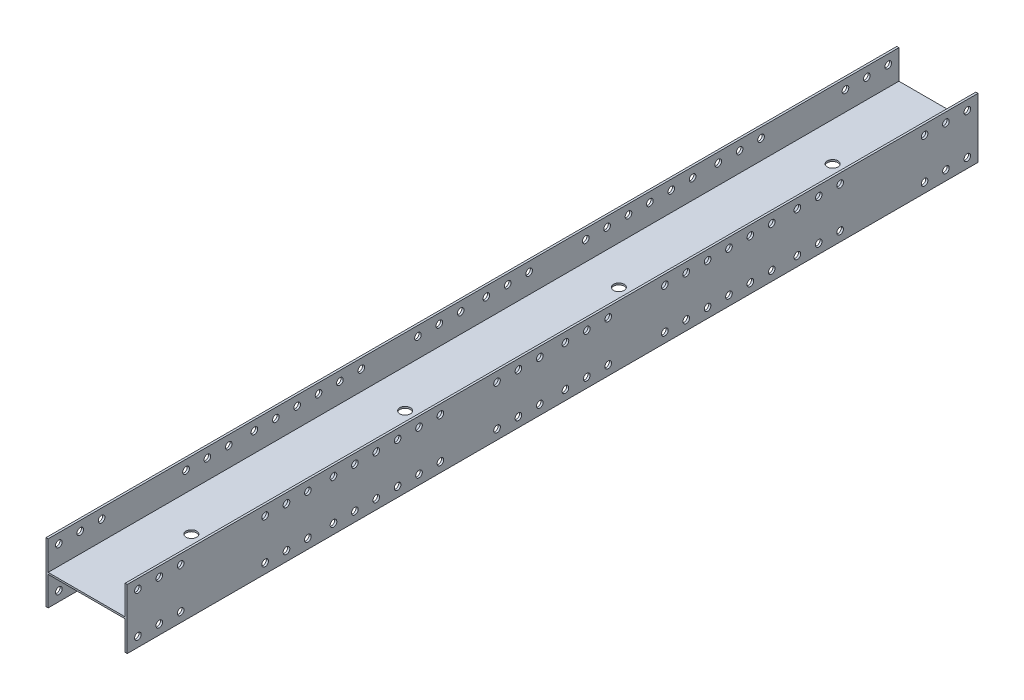
SolidWorks part; units mm, degrees
ref_plane "前视基准面" through (0, 0, 0) normal (0, 0, 1) x (1, 0, 0)
ref_plane "上视基准面" through (0, 0, 0) normal (0, 1, 0) x (1, 0, 0)
ref_plane "右视基准面" through (0, 0, 0) normal (1, 0, 0) x (0, 0, -1)
sketch "草图3" plane through (0, 0, 0) normal (0, 0, 1) x (1, 0, 0)
  line L1 (-420.0113, 0) -> (343.1369, 0) construction
  line L3 (0, 69.2779) -> (0, -66.7221) construction
  line L4 (180, -4) -> (-180, -4)
  line L5 (180, 4) -> (180, 140)
  line L6 (-180, 140) -> (-190, 140)
  line L7 (-190, 140) -> (-190, -140)
  line L8 (-190, -140) -> (-180, -140)
  line L9 (-180, -140) -> (-180, -4)
  line L10 (-180, 4) -> (180, 4)
  line L11 (-180, 4) -> (-180, 140)
  line L12 (180, -140) -> (180, -4)
  line L13 (190, -140) -> (180, -140)
  line L14 (190, 140) -> (190, -140)
  line L15 (180, 140) -> (190, 140)
  point P15 (0, -4)
  point P16 (0, 4)
  dimension "D1" = 280
  dimension "D2" = 10
  dimension "D3" = 10
  dimension "D4" = 380
  dimension "D5" = 8
extrude "拉伸1" add sketch "草图3" along normal mid plane 3980
sketch "草图6" plane through (0, 0, 0) normal (0, 1, 0) x (1, 0, 0)
  line L1 (0, 602.5985) -> (0, -4597.2067) construction
  line L2 (180, 0) -> (-49820, 0) construction
  line L6 (180, -1990) -> (180, 1990) construction
  line L7 (180, -1990) -> (-180, -1990) construction
  line L8 (-190, -1990) -> (-190, 1990) construction
  circle A0 centre (0, 500) radius 25
  circle A1 centre (0, 1500) radius 25
  circle A6 centre (0, -1500) radius 25
  circle A7 centre (0, -500) radius 25
  point P10 (180, 0)
  point P13 (-190, 0)
  dimension "D7" = 50
  dimension "D9" = 50
  dimension "D2" = 490
  dimension "D10" = 1000
extrude "拉伸2" cut sketch "草图6" against normal through all and the other way through all
sketch "草图4" plane through (0, 0, 0) normal (1, 0, 0) x (0, 0, -1)
  line L0 (-1990, 140) -> (1990, 140) construction
  line L2 (91.7311, 0) -> (-4448.0759, 0) construction
  line L3 (0, 140) -> (0, -49860) construction
  line L4 (-1990, -140) -> (1990, -140) construction
  line L6 (-1990, -140) -> (-1990, 140) construction
  circle A0 centre (-1940, 95) radius 15.5
  circle A1 centre (-1840, 95) radius 15.5
  circle A2 centre (-1740, 95) radius 15.5
  circle A3 centre (-1345, 95) radius 15.5
  circle A4 centre (-1245, 95) radius 15.5
  circle A5 centre (-1145, 95) radius 15.5
  circle A6 centre (-260, 95) radius 15.5
  circle A7 centre (-160, 95) radius 15.5
  circle A8 centre (-60, 95) radius 15.5
  circle A9 centre (-525, -95) radius 15.5
  circle A10 centre (-625, -95) radius 15.5
  circle A11 centre (-725, -95) radius 15.5
  circle A12 centre (-825, -95) radius 15.5
  circle A13 centre (-925, -95) radius 15.5
  circle A14 centre (-1025, -95) radius 15.5
  circle A15 centre (-60, -95) radius 15.5
  circle A16 centre (-160, -95) radius 15.5
  circle A17 centre (-260, -95) radius 15.5
  circle A18 centre (-1145, -95) radius 15.5
  circle A19 centre (-1245, -95) radius 15.5
  circle A20 centre (-1345, -95) radius 15.5
  circle A21 centre (-1740, -95) radius 15.5
  circle A22 centre (-1840, -95) radius 15.5
  circle A23 centre (-1940, -95) radius 15.5
  circle A24 centre (-1025, 95) radius 15.5
  circle A25 centre (-925, 95) radius 15.5
  circle A26 centre (-825, 95) radius 15.5
  circle A27 centre (-725, 95) radius 15.5
  circle A28 centre (-625, 95) radius 15.5
  circle A29 centre (-525, 95) radius 15.5
  circle A30 centre (525, 95) radius 15.5
  circle A31 centre (625, 95) radius 15.5
  circle A32 centre (725, 95) radius 15.5
  circle A33 centre (825, 95) radius 15.5
  circle A34 centre (925, 95) radius 15.5
  circle A35 centre (1025, 95) radius 15.5
  circle A36 centre (1940, -95) radius 15.5
  circle A37 centre (1840, -95) radius 15.5
  circle A38 centre (1740, -95) radius 15.5
  circle A39 centre (1345, -95) radius 15.5
  circle A40 centre (1245, -95) radius 15.5
  circle A41 centre (1145, -95) radius 15.5
  circle A42 centre (260, -95) radius 15.5
  circle A43 centre (160, -95) radius 15.5
  circle A44 centre (60, -95) radius 15.5
  circle A45 centre (1025, -95) radius 15.5
  circle A46 centre (925, -95) radius 15.5
  circle A47 centre (825, -95) radius 15.5
  circle A48 centre (725, -95) radius 15.5
  circle A49 centre (625, -95) radius 15.5
  circle A50 centre (525, -95) radius 15.5
  circle A51 centre (60, 95) radius 15.5
  circle A52 centre (160, 95) radius 15.5
  circle A53 centre (260, 95) radius 15.5
  circle A54 centre (1145, 95) radius 15.5
  circle A55 centre (1245, 95) radius 15.5
  circle A56 centre (1345, 95) radius 15.5
  circle A57 centre (1740, 95) radius 15.5
  circle A58 centre (1840, 95) radius 15.5
  circle A59 centre (1940, 95) radius 15.5
  point P23 (0, 140)
  point P133 (0, -140)
  dimension "D6" = 31
  dimension "D7" = 395
  dimension "D8" = 31
  dimension "D1" = 45
  dimension "D2" = 95
  dimension "D3" = 50
  dimension "D4" = 100
  dimension "D5" = 100
  dimension "D9" = 100
  dimension "D10" = 100
  dimension "D11" = 265
  dimension "D12" = 120
  dimension "D13" = 100
  dimension "D15" = 100
extrude "拉伸6" cut sketch "草图4" against normal through all and the other way through all
